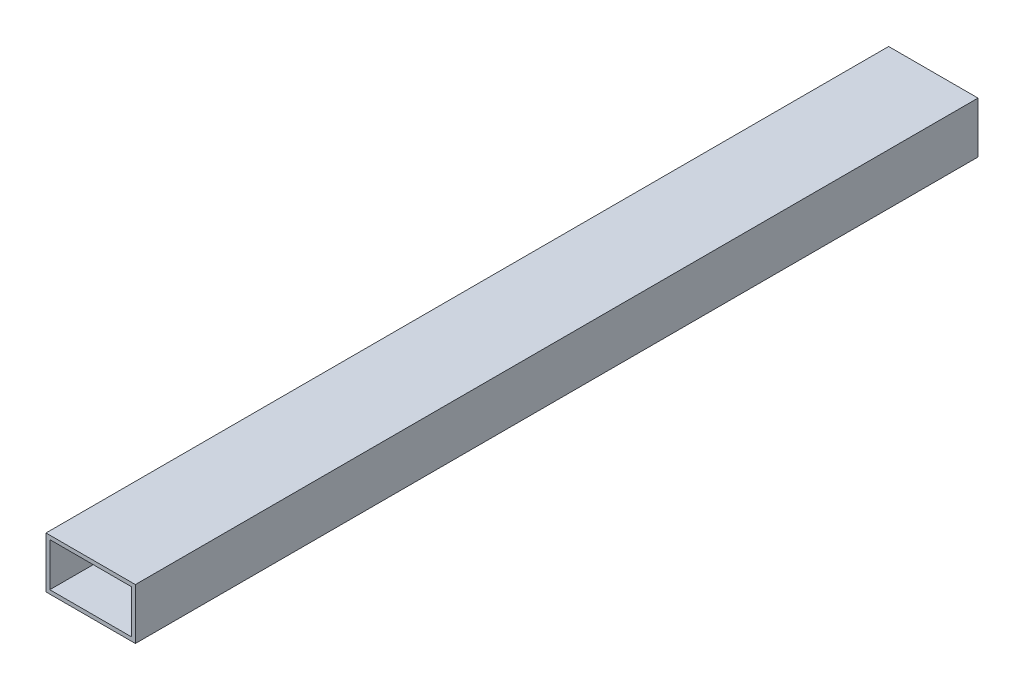
SolidWorks part; units mm, degrees
material "AISI 1020 Acier laminé à froid"
ref_plane "Plan de face" through (0, 0, 0) normal (0, 0, 1) x (1, 0, 0)
ref_plane "Plan de dessus" through (0, 0, 0) normal (0, 1, 0) x (1, 0, 0)
ref_plane "Plan de droite" through (0, 0, 0) normal (1, 0, 0) x (0, 0, -1)
sketch "Esquisse1" plane through (0, 0, 0) normal (0, 0, 1) x (1, 0, 0)
  line L1 (0, 0) -> (35, 0)
  line L2 (0, 0) -> (0, 20)
  line L3 (0, 20) -> (35, 20)
  line L4 (35, 0) -> (35, 20)
  line L5 (1.5, 18.5) -> (33.5, 18.5)
  line L6 (1.5, 18.5) -> (1.5, 1.5)
  line L7 (1.5, 1.5) -> (33.5, 1.5)
  line L8 (33.5, 18.5) -> (33.5, 1.5)
  dimension "D1" = 35
  dimension "D2" = 20
  dimension "D3" = 1.5
  dimension "D4" = 1.5
  dimension "D5" = 1.5
  dimension "D6" = 1.5
extrude "Boss.-Extru.1" add sketch "Esquisse1" along normal blind 330
sketch "Esquisse2" plane through (0, 0, 0) normal (0, 1, 0) x (1, 0, 0)
  line L0 (0, -330) -> (35, -295)
  line L1 (35, -330) -> (35, 0) construction
  line L2 (0, -330) -> (35, -330)
  line L3 (35, -330) -> (35, -295)
  dimension "D1" = 45
extrude "Enlèv. mat.-Extru.1" [suppressed] cut sketch "Esquisse2" along normal through all
sketch "Esquisse4" plane through (0, 0, 0) normal (0, 1, 0) x (1, 0, 0)
  line L0 (0, 0) -> (35, -35)
  line L1 (35, -330) -> (35, 0) construction
  line L2 (35, -35) -> (35, 0)
  line L3 (35, 0) -> (0, 0)
  dimension "D1" = 45
extrude "Enlèv. mat.-Extru.3" [suppressed] cut sketch "Esquisse4" along normal through all
